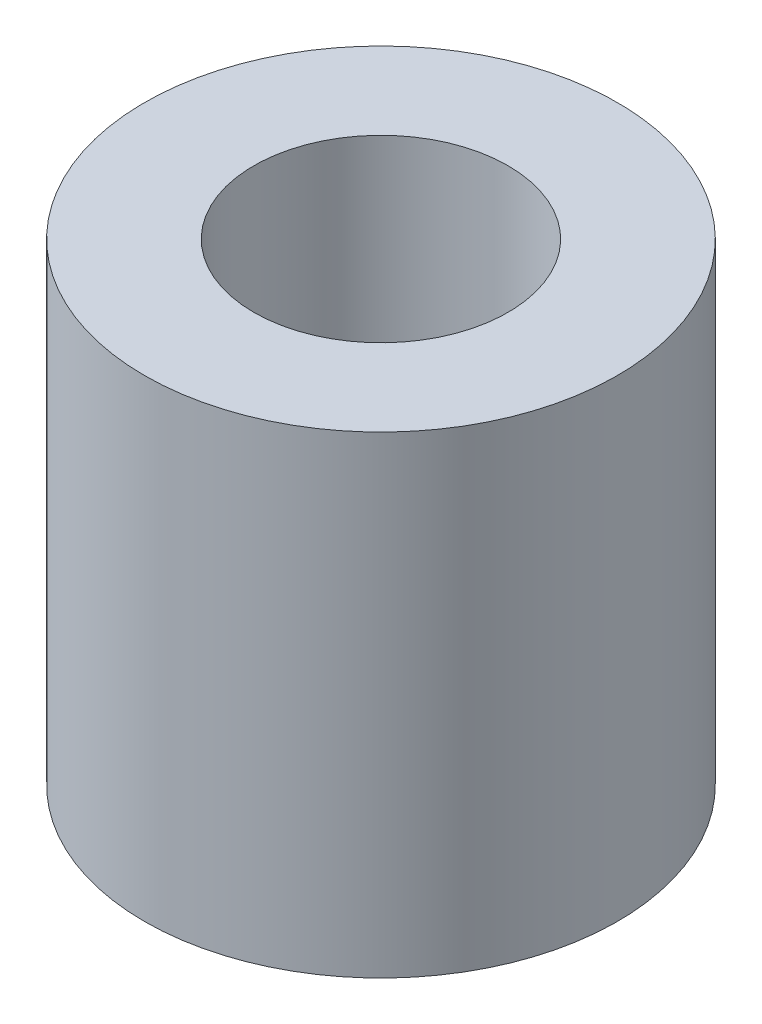
SolidWorks part; units mm, degrees
material "Aleación 6061"
ref_plane "Alzado" through (0, 0, 0) normal (0, 0, 1) x (1, 0, 0)
ref_plane "Planta" through (0, 0, 0) normal (0, 1, 0) x (1, 0, 0)
ref_plane "Vista lateral" through (0, 0, 0) normal (1, 0, 0) x (0, 0, -1)
sketch "Croquis1" plane through (0, 0, 0) normal (0, 1, 0) x (1, 0, 0)
  circle A0 centre (40, -195.45) radius 4
  dimension "D1" = 8
  dimension "D2" = 40
  dimension "D3" = 195.45
extrude "Tubo_D8" add sketch "Croquis1" along normal blind 8 from offset 4
sketch "Croquis2" plane through (0, 0, 0) normal (0, 1, 0) x (1, 0, 0)
  circle A0 centre (40, -195.45) radius 2.15
  dimension "D1" = 4.3
  dimension "D2" = 40
  dimension "D3" = 195.45
extrude "Paso_M4" cut sketch "Croquis2" along normal blind 8 from offset 4
